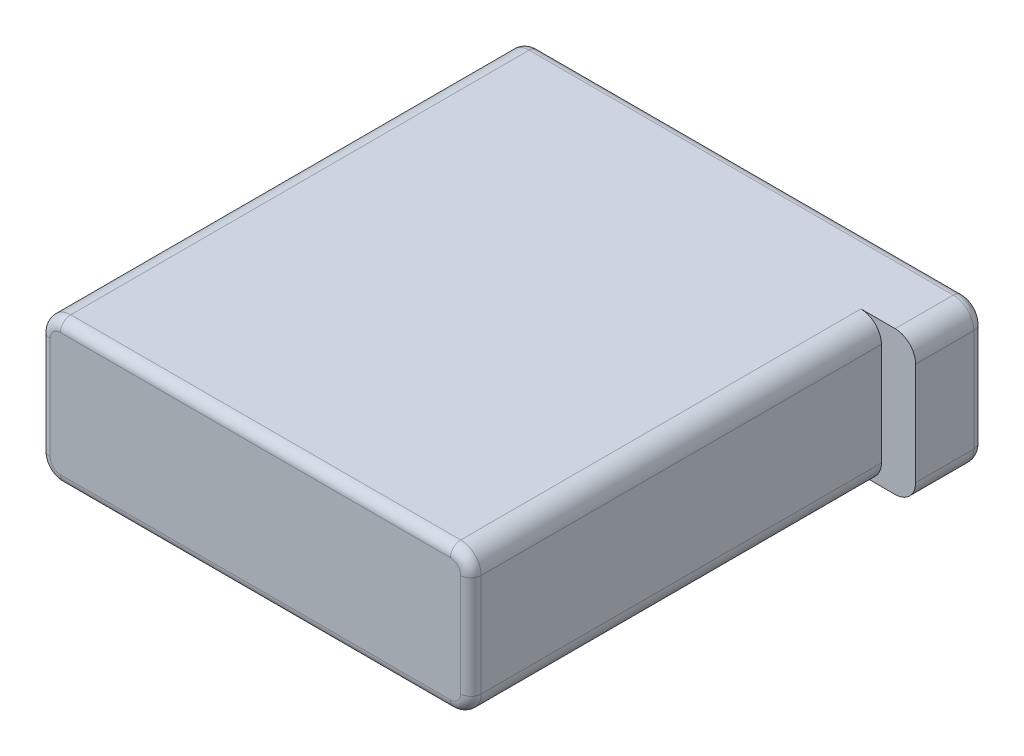
SolidWorks part; units mm, degrees
material "Zinc AC41A Alloy, As Cast"
ref_plane "Front Plane" through (0, 0, 0) normal (0, 0, 1) x (1, 0, 0)
ref_plane "Top Plane" through (0, 0, 0) normal (0, 1, 0) x (1, 0, 0)
ref_plane "Right Plane" through (0, 0, 0) normal (1, 0, 0) x (0, 0, -1)
sketch "Sketch1" plane through (0, 0, 0) normal (0, 1, 0) x (1, 0, 0)
  line L1 (-31.5, 35) -> (31.5, 35)
  line L2 (-31.5, 35) -> (-31.5, -35)
  line L3 (-31.5, -35) -> (31.5, -35)
  line L4 (31.5, 35) -> (31.5, -35)
  line L5 (-31.5, 35) -> (31.5, -35) construction
  line L6 (-31.5, -35) -> (31.5, 35) construction
  point P0 (0, 0)
  dimension "D1" = 70
  dimension "D2" = 63
extrude "Boss-Extrude1" add sketch "Sketch1" along normal blind 21 contours L1 L4 L3 L2
sketch "Sketch2" plane through (31.5, 0, 0) normal (1, 0, 0) x (0, 0, -1)
  line L0 (25, 21) -> (25, 0)
  line L4 (-35, 0) -> (35, 0)
  line L5 (35, 0) -> (35, 21)
  line L6 (35, 21) -> (-35, 21)
  line L7 (-35, 21) -> (-35, 0)
  line L8 (-35, 0) -> (35, 0)
  line L9 (35, 0) -> (35, 21)
  line L10 (35, 21) -> (-35, 21)
  line L11 (-35, 21) -> (-35, 0)
  line M5 (-35, 0) -> (35, 0)
  line M6 (35, 0) -> (35, 21)
  line M7 (35, 21) -> (-35, 21)
  dimension "D2" = 10
  dimension "D1" = 0
extrude "Boss-Extrude2" add sketch "Sketch2" along normal blind 5 contours L0 M7 M5 M6
fillet "Fillet3" radius 3 6 edges at (-31.5, 0, 0) (-31.5, 21, 0) (36.5, 21, -30) (36.5, 0, -30) (31.5, 0, 5) (31.5, 21, 5)
fillet "Fillet4" radius 1.5 16 edges at (-30.6213, 20.1213, 35) (0, 21, 35) (30.6213, 20.1213, 35) (31.5, 10.5, 35) (30.6213, 0.8787, 35) (0, 0, 35) (-30.6213, 0.8787, 35) (-31.5, 10.5, 35) (35.6213, 0.8787, -35) (36.5, 10.5, -35) (35.6213, 20.1213, -35) (2.5, 21, -35) (-30.6213, 20.1213, -35) (-31.5, 10.5, -35) (-30.6213, 0.8787, -35) (2.5, 0, -35)
